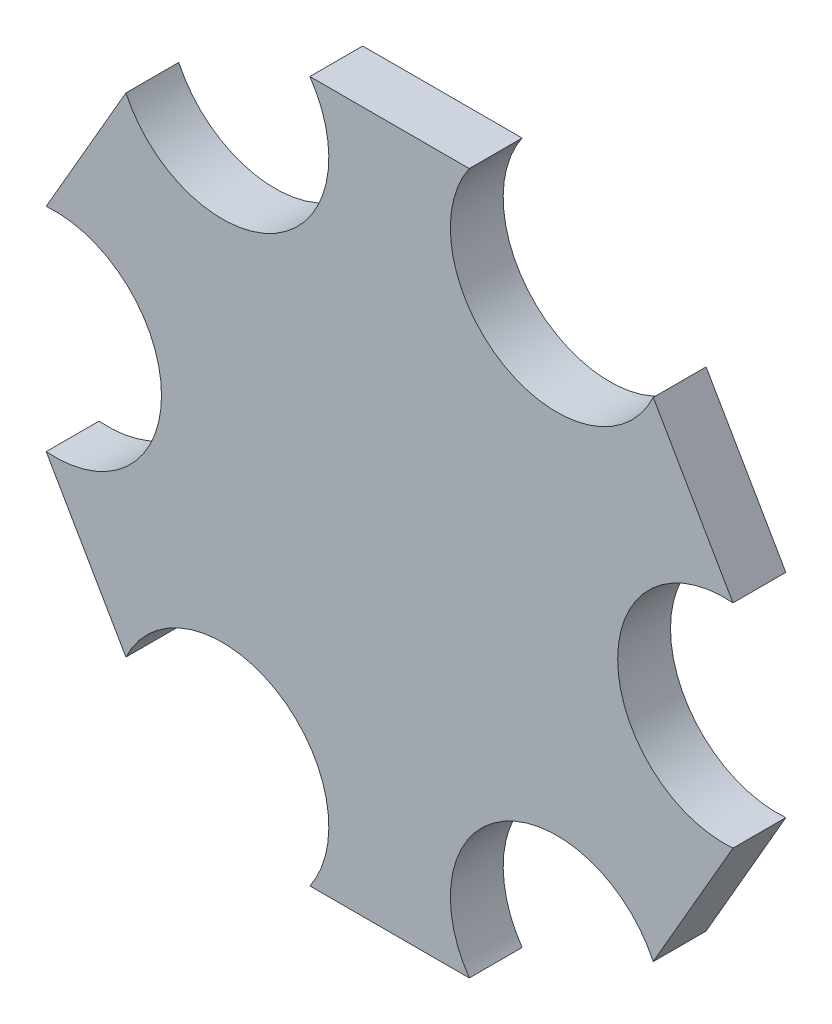
SolidWorks part; units mm, degrees
ref_plane "前视基准面" through (0, 0, 0) normal (0, 0, 1) x (1, 0, 0)
ref_plane "上视基准面" through (0, 0, 0) normal (0, 1, 0) x (1, 0, 0)
ref_plane "右视基准面" through (0, 0, 0) normal (1, 0, 0) x (0, 0, -1)
sketch "草图1" plane through (0, 0, 0) normal (0, 0, 1) x (1, 0, 0)
  line L1 (11.4893, 0) -> (5.7446, 9.95)
  line L2 (5.7446, 9.95) -> (-5.7446, 9.95)
  line L3 (-5.7446, 9.95) -> (-11.4893, 0)
  line L4 (-11.4893, 0) -> (-5.7446, -9.95)
  line L5 (-5.7446, -9.95) -> (5.7446, -9.95)
  line L6 (5.7446, -9.95) -> (11.4893, 0)
  circle A0 centre (0, 0) radius 9.95 construction
  point P21 (0, 0)
  dimension "D1" = 19.9
extrude "凸台-拉伸1" add sketch "草图1" along normal blind 1.5 contours L2 L3 L4 L5 L6 L1
sketch "草图2" plane through (0, 0, 1.5) normal (0, 0, 1) x (1, 0, 0)
  circle A0 centre (-9.5, 0) radius 3.0251
  circle A1 centre (-4.75, 8.2272) radius 3.0251
  circle A2 centre (4.75, 8.2272) radius 3.0251
  circle A3 centre (9.5, 0) radius 3.0251
  circle A4 centre (4.75, -8.2272) radius 3.0251
  circle A5 centre (-4.75, -8.2272) radius 3.0251
  point P15 (0, 0)
  dimension "D1" = 9.5
  dimension "D2" = 6.0501
  dimension "D3" = 6
extrude "切除-拉伸1" cut sketch "草图2" against normal through all
sketch "草图4" plane through (0, 0, 0) normal (1, 0, 0) x (0, 0, -1)
  line L0 (0, -3.0251) -> (0, 3.0251) construction
  line L1 (0, 0) -> (3.62, 0)
  arc A0 (0, 3.62) -> (3.62, 0) centre (0, 0) cw
  dimension "D2" = 3.62
  dimension "D3" = 3.62
revolve "旋转-薄壁2" add sketch "草图4" angle 360 about L1 wall 0.1
